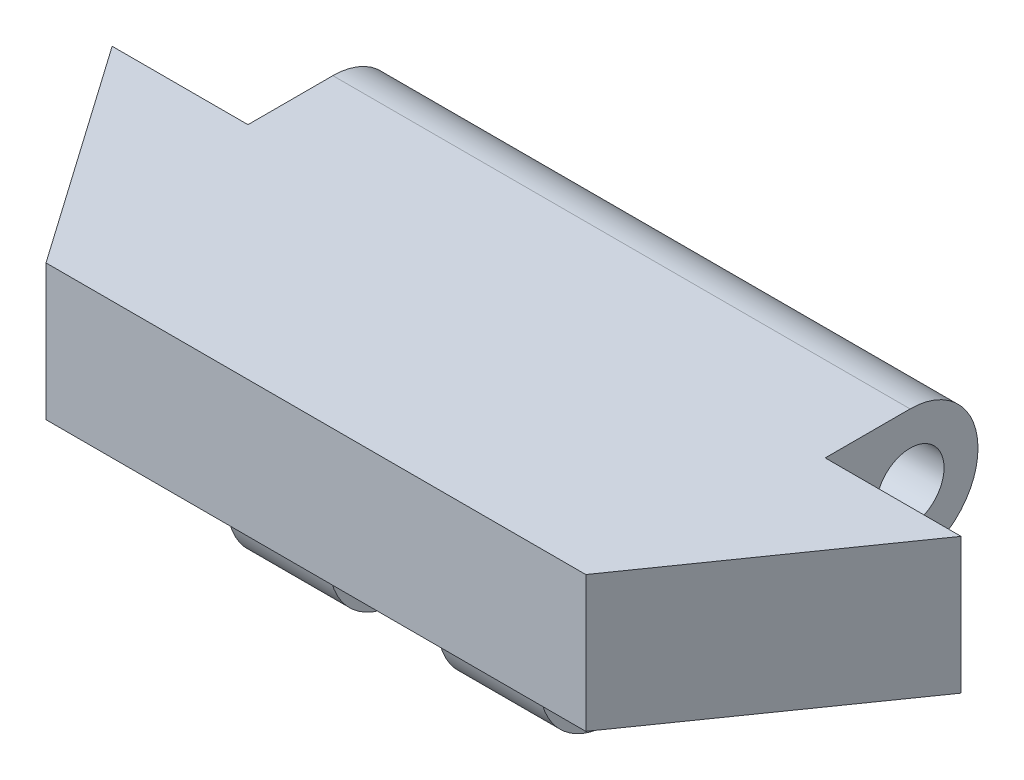
SolidWorks part; units mm, degrees
ref_plane "Front Plane" through (0, 0, 0) normal (0, 0, 1) x (1, 0, 0)
ref_plane "Top Plane" through (0, 0, 0) normal (0, 1, 0) x (1, 0, 0)
ref_plane "Right Plane" through (0, 0, 0) normal (1, 0, 0) x (0, 0, -1)
sketch "Sketch1" plane through (0, 0, 0) normal (0, 1, 0) x (1, 0, 0)
  line L0 (0, 0) -> (4.5513, -6.5)
  line L1 (0, 0) -> (25, 0)
  line L3 (4.5513, -6.5) -> (20.4487, -6.5)
  line L5 (12.5, 0) -> (12.5, -6.5) construction
  line L6 (25, 0) -> (20.4487, -6.5)
  dimension "D1" = 25
  dimension "D2" = 6.5
  dimension "D3" = 55
extrude "Boss-Extrude1" add sketch "Sketch1" along normal blind 4
sketch "Sketch2" plane through (0, 0, 0) normal (1, 0, 0) x (0, 0, -1)
  line L1 (0, 0) -> (2.5, 0)
  line L2 (0, 0) -> (0, 4)
  line L3 (0, 4) -> (2.5, 4)
  arc A0 (2.5, 0) -> (2.5, 4) centre (2.5, 2) ccw
  circle A1 centre (2.5, 2) radius 1
  dimension "D3" = 2
  dimension "D1" = 2.5
extrude "Boss-Extrude2" add sketch "Sketch2" along normal blind 17 from offset 4
sketch "Sketch3" plane through (0, 0, 0) normal (1, 0, 0) x (0, 0, -1)
  line L0 (-6.5, 4) -> (-6.5, 0) construction
  line L1 (-4.5, 0) -> (-0.5, 0)
  line L2 (-4.5, 0) -> (-4.5, -1.5)
  line L4 (-0.5, 0) -> (-0.5, -1.5)
  line L5 (0, 0) -> (-6.5, 0) construction
  arc A0 (-4.5, -1.5) -> (-0.5, -1.5) centre (-2.5, -1.5) ccw
  circle A1 centre (-2.5, -1.5) radius 1
  dimension "D2" = 2
  dimension "D3" = 2
  dimension "D1" = 1.5
  dimension "D4" = 2
extrude "Boss-Extrude3" add sketch "Sketch3" along normal blind 4.6 and the other way blind 4.6 from offset 12.5
sketch "Sketch4" plane through (0, 0, 6.5) normal (0, 0, 1) x (1, 0, 0)
  line L0 (7.9, -3.5) -> (17.1, -3.5) construction
  line L1 (14.1, 0) -> (10.9, 0)
  line L2 (14.1, 0) -> (14.1, -3.5)
  line L3 (14.1, -3.5) -> (10.9, -3.5)
  line L4 (10.9, 0) -> (10.9, -3.5)
  line L5 (12.5, 4) -> (12.5, -3.5) construction
  line L7 (4.5513, 4) -> (20.4487, 4) construction
  line L8 (4.5513, 0) -> (20.4487, 0) construction
  point P10 (12.5, 0)
  dimension "D1" = 3.2
extrude "Cut-Extrude1" cut sketch "Sketch4" against normal up to next
sketch "Sketch5" plane through (14.1, 0, 0) normal (-1, 0, 0) x (0, 0, 1)
  line L0 (1.9838, 0.9461) -> (-2.5, 0)
  line L1 (0, 0) -> (-2.5, 0) construction
  line L2 (-2.5, 0) -> (0.5, 0)
  arc A0 (0.5, 0) -> (1.9838, 0.9461) centre (2.5, -1.5) ccw
  arc A1 (-2.5, 4) -> (-2.5, 0) centre (-2.5, 2) ccw construction
  circle A2 centre (2.5, -1.5) radius 1 construction
  dimension "D1" = 5
extrude "Cut-Extrude2" cut sketch "Sketch5" along normal up to surface (3.2 mm away) up to face at (10.9, -2.5, 2.5)
